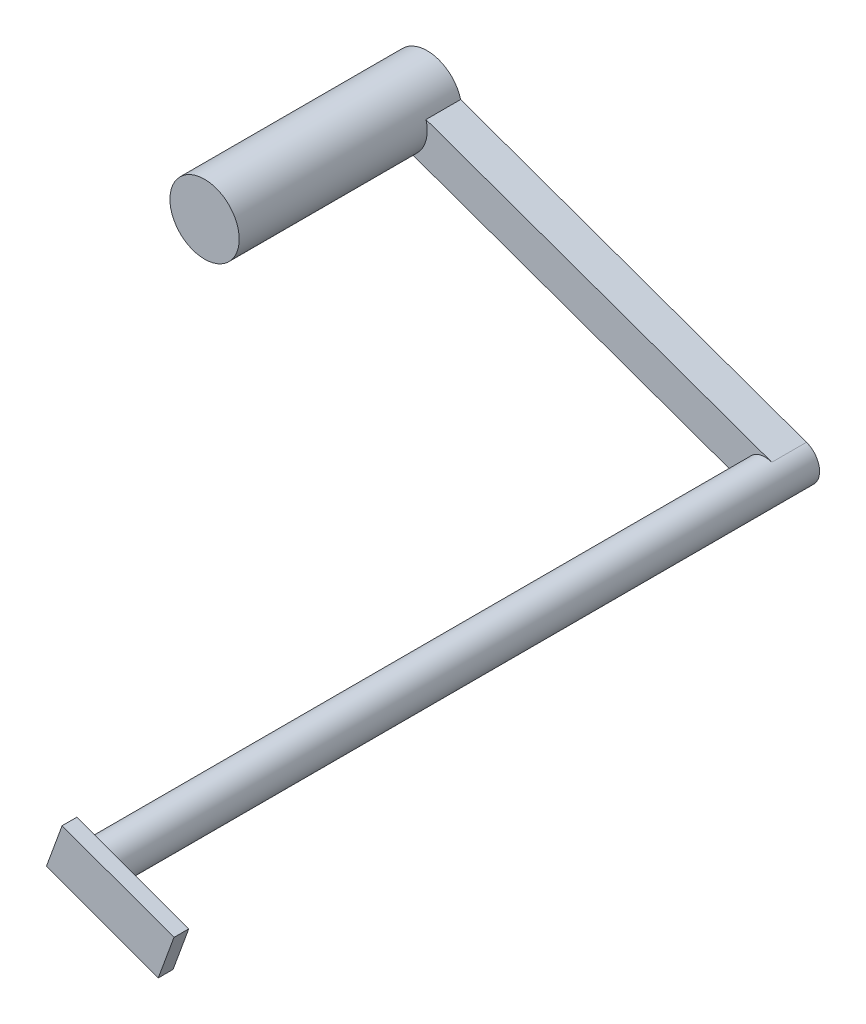
SolidWorks part; units mm, degrees
ref_plane "前视基准面" through (0, 0, 0) normal (0, 0, 1) x (1, 0, 0)
ref_plane "上视基准面" through (0, 0, 0) normal (0, 1, 0) x (1, 0, 0)
ref_plane "右视基准面" through (0, 0, 0) normal (1, 0, 0) x (0, 0, -1)
other "Configuration Table"
sketch "草图1" plane through (0, 0, 0) normal (0, 0, 1) x (1, 0, 0)
  circle A0 centre (-86.6066, -63.7835) radius 7
extrude "凸台-拉伸1" add sketch "草图1" along normal blind 45
sketch "草图3" plane through (0, 0, 0) normal (0, 0, -1) x (-1, 0, 0)
  line L0 (86.6066, -63.7835) -> (11.2929, -90.7622) construction
  line L1 (87.9556, -67.5492) -> (12.6419, -94.5278)
  line L2 (85.2577, -60.0178) -> (9.944, -86.9965)
  arc A0 (87.9556, -67.5492) -> (85.2577, -60.0178) centre (86.6066, -63.7835) ccw
  arc A1 (9.944, -86.9965) -> (12.6419, -94.5278) centre (11.2929, -90.7622) ccw
  point P2 (48.9498, -77.2728)
extrude "凸台-拉伸2" add sketch "草图3" against normal blind 7
sketch "草图7" plane through (0, 0, 7) normal (0, 0, 1) x (1, 0, 0)
  circle A3 centre (-11.2929, -90.7622) radius 4
extrude "凸台-拉伸3" add sketch "草图7" along normal blind 135
sketch "草图8" plane through (0, 0, 142) normal (0, 0, 1) x (1, 0, 0)
  line L0 (-85.2459, -60.0221) -> (-19.7506, -83.9496) construction
  line L1 (-79.8497, -61.9551) -> (-9.944, -86.9965) construction
  line L2 (2.7174, -96.4164) -> (8.6404, -80.2036) construction
  line L3 (2.8901, -95.9437) -> (-11.2929, -90.7622) construction
  line L4 (-15.3941, -84.336) -> (7.2076, -92.5931)
  line L5 (7.2076, -92.5931) -> (4.0309, -101.2883)
  line L7 (4.0309, -101.2883) -> (-18.5708, -93.0312)
  line L8 (-18.5708, -93.0312) -> (-15.3941, -84.336)
  point P7 (3.6853, -102.2343)
  point P11 (-18.5708, -93.0312)
extrude "凸台-拉伸4" add sketch "草图8" along normal blind 3
